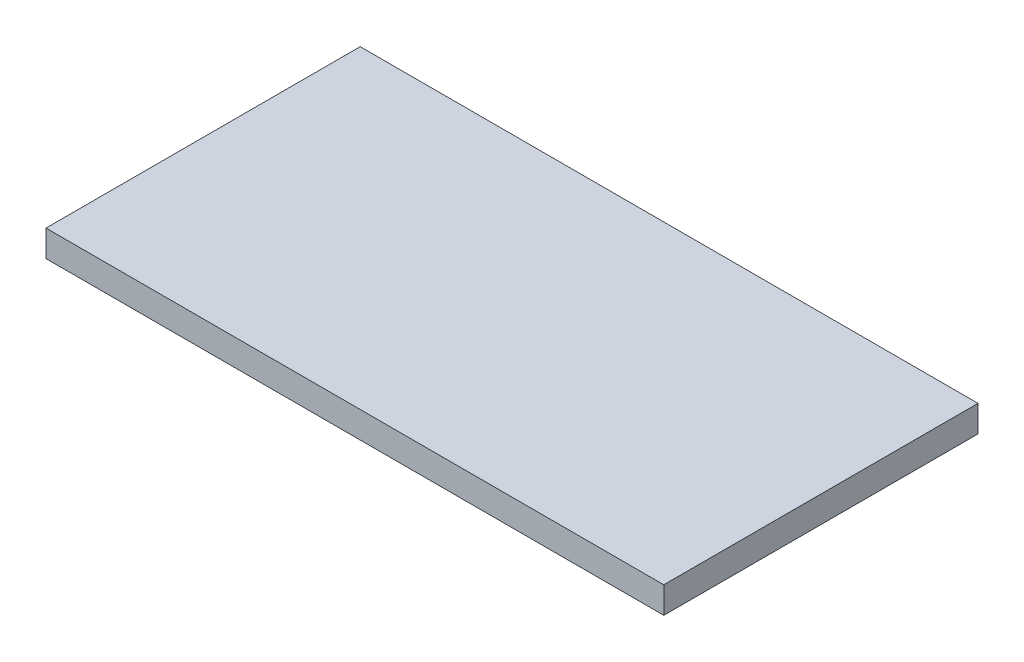
SolidWorks part; units mm, degrees
material "Thornel VCB-20 碳布"
ref_plane "前视基准面" through (0, 0, 0) normal (0, 0, 1) x (1, 0, 0)
ref_plane "上视基准面" through (0, 0, 0) normal (0, 1, 0) x (1, 0, 0)
ref_plane "右视基准面" through (0, 0, 0) normal (1, 0, 0) x (0, 0, -1)
other "Configuration Table"
sketch "草图1" plane through (0, 0, 0) normal (0, 1, 0) x (1, 0, 0)
  line L1 (0, 0) -> (70, 0)
  line L2 (0, 0) -> (0, -35.6)
  line L3 (0, -35.6) -> (70, -35.6)
  line L4 (70, 0) -> (70, -35.6)
  dimension "D1" = 70
  dimension "D2" = 35.6
extrude "凸台-拉伸1" add sketch "草图1" along normal blind 3
